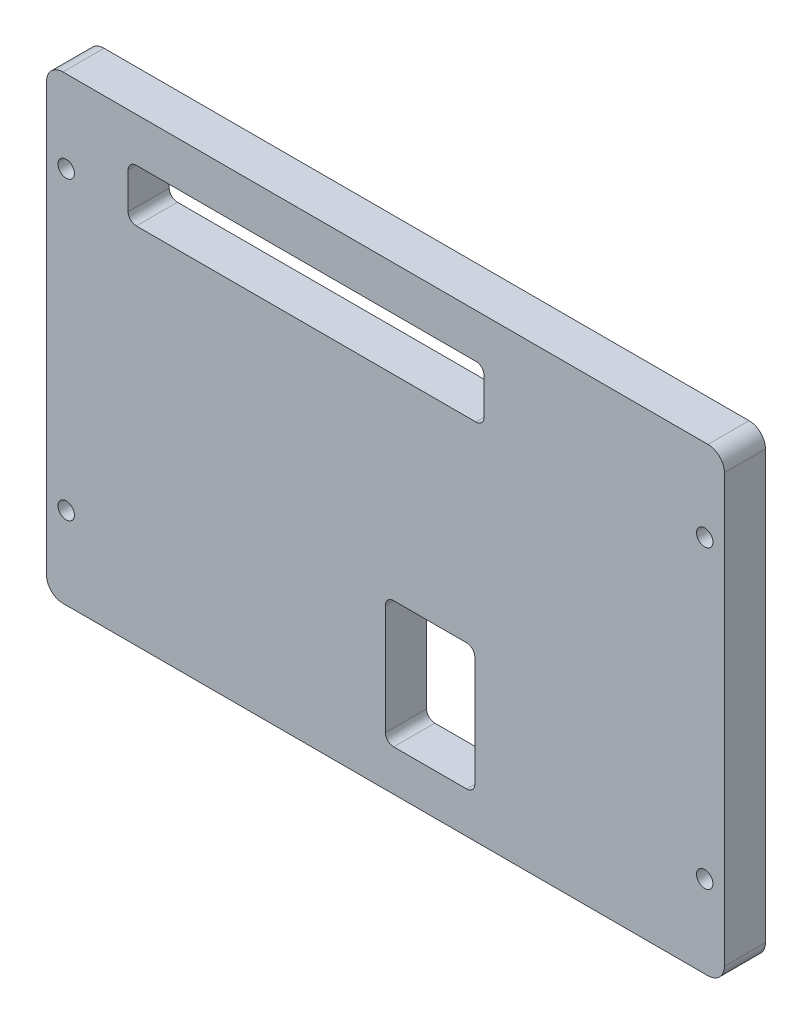
SolidWorks part; units mm, degrees
ref_plane "Front Plane" through (0, 0, 0) normal (0, 0, 1) x (1, 0, 0)
ref_plane "Top Plane" through (0, 0, 0) normal (0, 1, 0) x (1, 0, 0)
ref_plane "Right Plane" through (0, 0, 0) normal (1, 0, 0) x (0, 0, -1)
sketch "Sketch1" plane through (0, 0, 0) normal (0, 0, 1) x (1, 0, 0)
  line L0 (46.0375, -29.21) -> (-2.7237, -29.21) construction
  line L1 (-38.5023, 28.7362) -> (13.9717, 28.7362)
  line L2 (-39.7723, 27.4662) -> (-39.7723, 21.8947)
  line L3 (-38.5023, 20.6247) -> (13.9717, 20.6247)
  line L4 (52.3875, -33.02) -> (52.3875, 33.02)
  line L5 (49.8475, 35.56) -> (-49.8475, 35.56)
  line L6 (-52.3875, 33.02) -> (-52.3875, -33.02)
  line L7 (-49.8475, -35.56) -> (49.8475, -35.56)
  line L8 (52.3875, -33.02) -> (52.3875, 33.02)
  line L9 (49.8475, 35.56) -> (-49.8475, 35.56)
  line L10 (-52.3875, 33.02) -> (-52.3875, -33.02)
  line L11 (-49.8475, -35.56) -> (49.8475, -35.56)
  line L12 (15.2417, 27.4662) -> (15.2417, 21.8947)
  line L13 (1.27, -9.6462) -> (12.5395, -9.6462)
  line L14 (0, -10.9162) -> (0, -27.94)
  line L15 (1.27, -29.21) -> (12.5395, -29.21)
  line L16 (13.8095, -10.9162) -> (13.8095, -27.94)
  arc A0 (1.27, -9.6462) -> (0, -10.9162) centre (1.27, -10.9162) ccw
  arc A1 (0, -27.94) -> (1.27, -29.21) centre (1.27, -27.94) ccw
  arc A2 (12.5395, -29.21) -> (13.8095, -27.94) centre (12.5395, -27.94) ccw
  arc A3 (12.5395, -9.6462) -> (13.8095, -10.9162) centre (12.5395, -10.9162) cw
  arc A4 (52.3875, 33.02) -> (49.8475, 35.56) centre (49.8475, 33.02) ccw
  arc A5 (-49.8475, 35.56) -> (-52.3875, 33.02) centre (-49.8475, 33.02) ccw
  arc A6 (-52.3875, -33.02) -> (-49.8475, -35.56) centre (-49.8475, -33.02) ccw
  arc A7 (49.8475, -35.56) -> (52.3875, -33.02) centre (49.8475, -33.02) ccw
  arc A8 (52.3875, 33.02) -> (49.8475, 35.56) centre (49.8475, 33.02) ccw
  arc A9 (-49.8475, 35.56) -> (-52.3875, 33.02) centre (-49.8475, 33.02) ccw
  arc A10 (-52.3875, -33.02) -> (-49.8475, -35.56) centre (-49.8475, -33.02) ccw
  arc A11 (49.8475, -35.56) -> (52.3875, -33.02) centre (49.8475, -33.02) ccw
  arc A12 (-38.5023, 28.7362) -> (-39.7723, 27.4662) centre (-38.5023, 27.4662) ccw
  arc A13 (-39.7723, 21.8947) -> (-38.5023, 20.6247) centre (-38.5023, 21.8947) ccw
  arc A14 (13.9717, 28.7362) -> (15.2417, 27.4662) centre (13.9717, 27.4662) cw
  arc A15 (13.9717, 20.6247) -> (15.2417, 21.8947) centre (13.9717, 21.8947) ccw
  point P28 (13.8095, -29.21)
  dimension "D2" = 1.27
  dimension "D1" = 0
extrude "Boss-Extrude1" add sketch "Sketch1" along normal blind 6.35
sketch "Sketch2" plane through (0, 0, 6.35) normal (0, 0, 1) x (1, 0, 0)
  line L0 (-46.0375, 29.21) -> (-46.0375, -29.21) construction
  line L1 (46.0375, -29.21) -> (46.0375, 29.21) construction
  line L2 (49.8475, 35.56) -> (-49.8475, 35.56) construction
  line L3 (-49.8475, -35.56) -> (49.8475, -35.56) construction
  circle A0 centre (-49.3395, -22.86) radius 1.27
  circle A1 centre (-49.3395, 22.86) radius 1.27
  circle A2 centre (49.3395, 22.86) radius 1.27
  circle A3 centre (49.3395, -22.86) radius 1.27
  point P12 (0, 0)
  point P13 (0, 0)
  point P14 (0, 0)
  point P17 (0, 0)
  point P18 (0, 0)
  dimension "D1" = 2.54
  dimension "D4" = 12.7
  dimension "D2" = 3.302
  dimension "D3" = 3.302
  dimension "D5" = 12.7
extrude "Cut-Extrude1" cut sketch "Sketch2" against normal through all
